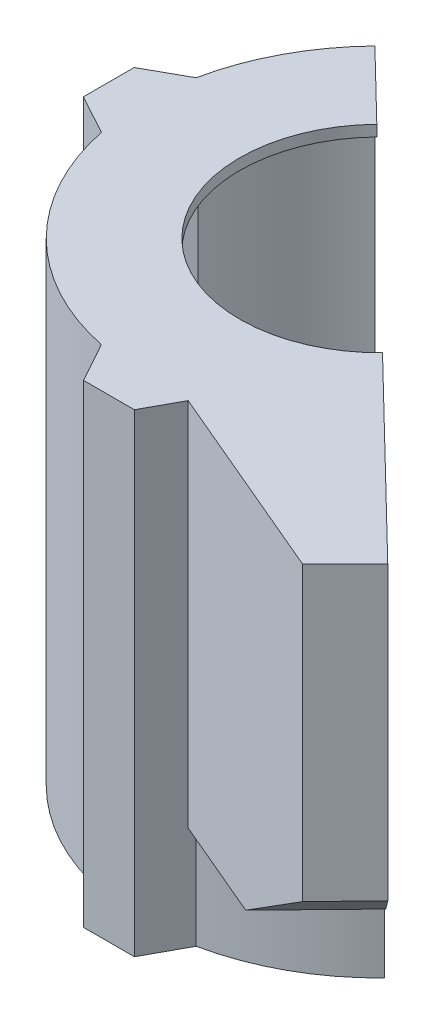
SolidWorks part; units mm, degrees
ref_plane "Alzado" through (0, 0, 0) normal (0, 0, 1) x (1, 0, 0)
ref_plane "Planta" through (0, 0, 0) normal (0, 1, 0) x (1, 0, 0)
ref_plane "Vista lateral" through (0, 0, 0) normal (1, 0, 0) x (0, 0, -1)
sketch "Croquis1" plane through (0, 0, 0) normal (0, 1, 0) x (1, 0, 0)
  line L0 (4, 58) -> (8.8071, 49.2182)
  line L1 (-4, 58) -> (4, 58)
  line L7 (-4, 58) -> (-8.8071, 49.2182)
  line L8 (58, 4) -> (58, -4)
  line L9 (58, 4) -> (49.2182, 8.8071)
  line L10 (58, -4) -> (49.2182, -8.8071)
  line L11 (4, -58) -> (-4, -58)
  line L12 (4, -58) -> (8.8071, -49.2182)
  line L13 (-4, -58) -> (-8.8071, -49.2182)
  line L14 (-58, -4) -> (-58, 4)
  line L15 (-58, -4) -> (-49.2182, -8.8071)
  line L16 (-58, 4) -> (-49.2182, 8.8071)
  arc A0 (-8.8071, 49.2182) -> (-49.2182, 8.8071) centre (0, 0) ccw
  arc A1 (-49.2182, -8.8071) -> (-8.8071, -49.2182) centre (0, 0) ccw
  arc A2 (49.2182, 8.8071) -> (8.8071, 49.2182) centre (0, 0) ccw
  arc A3 (8.8071, -49.2182) -> (49.2182, -8.8071) centre (0, 0) ccw
  point P3 (0, 50)
  point P25 (0, 0)
  dimension "D1" = 100
  dimension "D3" = 8
  dimension "D4" = 4
extrude "Saliente-Extruir1" add sketch "Croquis1" along normal blind 5
sketch "Croquis2" plane through (0, 5, 0) normal (0, 1, 0) x (1, 0, 0)
  line L0 (4, 58) -> (-4, 58) construction
  circle A0 centre (0, 52.7) radius 2.1
  circle A1 centre (52.7, 0) radius 2.1
  circle A2 centre (0, -52.7) radius 2.1
  circle A3 centre (-52.7, 0) radius 2.1
  point P13 (0, 0)
  dimension "D1" = 4.2
  dimension "D2" = 5.3
  dimension "D4" = 0
  dimension "D5" = 52.7
  dimension "D3" = 4
extrude "Cortar-Extruir1" cut sketch "Croquis2" against normal through all
cosmetic thread "Rosca cosmética5" parameters "D2"=5
cosmetic thread "Rosca cosmética6" parameters "D2"=5
cosmetic thread "Rosca cosmética7" parameters "D2"=5
cosmetic thread "Rosca cosmética8" parameters "D2"=5
sketch "Croquis3" plane through (0, 5, 0) normal (0, 1, 0) x (1, 0, 0)
  line L0 (0, 0) -> (33.9411, -33.9411) construction
  line L11 (20.5061, -34.6482) -> (34.6482, -20.5061)
  line L16 (20.5061, -34.6482) -> (33.234, -47.3762)
  line L23 (34.6482, -20.5061) -> (47.3762, -33.234)
  line L24 (20.5061, -34.6482) -> (47.3762, -33.234) construction
  line L25 (33.234, -47.3762) -> (34.6482, -20.5061) construction
  line L27 (33.234, -47.3762) -> (53.0768, -67.2189)
  line L28 (53.0768, -67.2189) -> (67.2189, -53.0768)
  line L29 (47.3762, -33.234) -> (67.2189, -53.0768)
  point P224 (33.9411, -56.9721)
  point P274 (21.2132, -31.2132)
  point P609 (21.2132, -48.2132)
  dimension "D1" = 18
  dimension "D2" = 20
  dimension "D3" = 48
extrude "Cortar-Extruir2" cut sketch "Croquis3" against normal through all
sketch "Croquis5" plane through (0, 5, 0) normal (0, 1, 0) x (1, 0, 0)
  line L9 (21.5541, -30.0393) -> (23.3345, -31.8198)
  line L11 (28.6251, -22.9683) -> (30.9862, -25.3293)
  line L12 (30.9862, -25.3293) -> (32.4004, -23.9151)
  line L13 (30.0393, -21.5541) -> (32.4004, -23.9151)
  line L14 (29.7686, -22.1503) -> (32.4004, -23.9151) construction
  line L15 (30.9862, -25.3293) -> (29.2214, -22.6975) construction
  line L17 (22.9683, -28.6251) -> (24.7487, -30.4056)
  line L20 (34.6482, -20.5061) -> (20.5061, -34.6482) construction
  line L21 (23.3345, -31.8198) -> (24.7487, -30.4056)
  line L22 (20.5061, -34.6482) -> (27.5699, -41.7121) construction
  line L23 (41.7121, -27.5699) -> (34.6482, -20.5061) construction
  circle A1 centre (-7.78, 7.78) radius 2.05
  circle A2 centre (7.78, 7.78) radius 2.05
  circle A3 centre (7.78, -7.78) radius 2.05
  circle A4 centre (-7.78, -7.78) radius 2.05
  arc A5 (30.0393, -21.5541) -> (28.6251, -22.9683) centre (28.1075, -21.0364) ccw
  arc A6 (22.9683, -28.6251) -> (21.5541, -30.0393) centre (21.0364, -28.1075) ccw
  point P13 (0, 0)
  dimension "D1" = 4.1
  dimension "D5" = 4
  dimension "D6" = 4
  dimension "D2" = 7.78
  dimension "D3" = 7.78
  dimension "D7" = 4.25
  dimension "D8" = 4.25
  dimension "D9" = 5
  dimension "D10" = 5
  dimension "D12" = 2
  dimension "D4" = 4
extrude "Cortar-Extruir4" cut sketch "Croquis5" against normal through all
cosmetic thread "Rosca cosmética1" parameters "D2"=5
cosmetic thread "Rosca cosmética2" parameters "D2"=5
cosmetic thread "Rosca cosmética3" parameters "D2"=5
cosmetic thread "Rosca cosmética4" parameters "D2"=5
sketch "Croquis7" plane through (0, 5, 0) normal (0, 1, 0) x (1, 0, 0)
  line L6 (68.5894, -54.4472) -> (54.4472, -68.5894)
  line L7 (48.7904, -62.9325) -> (62.9325, -48.7904)
  line L8 (68.5894, -54.4472) -> (49.2182, -8.8071)
  line L9 (34.6482, -20.5061) -> (31.8198, -23.3345) construction
  line L10 (48.7904, -62.9325) -> (27.5699, -41.7121)
  line L11 (62.9325, -48.7904) -> (41.7121, -27.5699)
  line L12 (41.7121, -27.5699) -> (46.423, -18.5717)
  line L13 (27.5699, -41.7121) -> (18.5717, -46.423)
  line L14 (49.2182, -8.8071) -> (46.423, -18.5717)
  line L15 (54.4472, -68.5894) -> (8.8071, -49.2182)
  line L16 (8.8071, -49.2182) -> (18.5717, -46.423)
  arc A0 (41.7121, -27.5699) -> (49.2182, -8.8071) centre (0, 0) ccw construction
  arc A1 (8.8071, -49.2182) -> (27.5699, -41.7121) centre (0, 0) ccw construction
  dimension "D1" = 8
  dimension "D2" = 40
extrude "Saliente-Extruir2" add sketch "Croquis7" against normal through all
sketch "Croquis8" plane through (0, 5, 0) normal (0, 1, 0) x (1, 0, 0)
  line L0 (62.9325, -48.7904) -> (48.7904, -62.9325) construction
  line L5 (54.2831, -59.94) -> (51.4902, -57.1471)
  line L6 (51.4902, -57.1471) -> (50.076, -58.5613)
  line L8 (55.8008, -67.5537) -> (55.1474, -63.8416) construction
  line L9 (55.8008, -56.19) -> (55.1474, -59.9021) construction
  line L11 (57.3718, -51.715) -> (58.7861, -50.3008)
  line L12 (57.3718, -51.715) -> (59.94, -54.2831)
  line L14 (58.7861, -50.3008) -> (61.3542, -52.8689)
  line L15 (54.4541, -59.9021) -> (53.8008, -56.19) construction
  line L18 (54.4541, -63.8416) -> (53.8008, -67.5537) construction
  line L19 (52.8689, -61.3542) -> (50.076, -58.5613)
  line L21 (62.9325, -48.7904) -> (48.7904, -62.9325) construction
  arc A3 (59.94, -54.2831) -> (61.3542, -52.8689) centre (61.8718, -54.8008) ccw
  arc A6 (52.8689, -61.3542) -> (54.2831, -59.94) centre (54.8008, -61.8718) ccw
  dimension "D1" = 4
  dimension "D3" = 3.5
  dimension "D4" = 3.5
  dimension "D7" = 2
  dimension "D8" = 2
extrude "Cortar-Extruir10" cut sketch "Croquis8" against normal through all
sketch "Croquis15" plane through (0, 0, 0) normal (0, -1, 0) x (1, 0, 0)
  line L2 (-1.1111, -20.4699) -> (-1.1111, -22.4725)
  line L4 (1.1111, -20.4699) -> (1.1111, -22.4725)
  arc A0 (1.1111, -22.4725) -> (-1.1111, -22.4725) centre (0, 0) ccw
  arc A1 (1.1111, -20.4699) -> (-1.1111, -20.4699) centre (0, 0) ccw
  point P4 (0, -19.25)
  dimension "D1" = 45
  dimension "D2" = 41
  dimension "D4" = 19.25
  dimension "D5" = 0
extrude "Saliente-Extruir4" add sketch "Croquis15" along normal blind 4
sketch "Croquis16" plane through (0, 0, 0) normal (0, -1, 0) x (1, 0, 0)
  line L0 (1.1111, -20.4699) -> (1.1111, -22.4725) construction
  line L1 (-1.1111, -20.4699) -> (-1.1111, -22.4725)
  line L2 (1.1111, -20.4699) -> (1.1111, -22.4725)
  arc A0 (-1.1111, -22.4725) -> (1.1111, -22.4725) centre (0, 0) ccw
  arc A1 (1.1111, -22.4725) -> (-1.1111, -22.4725) centre (0, 0) ccw construction
  arc A2 (-1.1111, -20.4699) -> (1.1111, -20.4699) centre (0, 0) ccw
extrude "Saliente-Extruir5" add sketch "Croquis16" along normal blind 4
sketch "Croquis17" plane through (0, 0, 0) normal (0, -1, 0) x (1, 0, 0)
  line L2 (0, 0) -> (42.43, 0) construction
  circle A2 centre (42.43, 0) radius 2.4
  circle A3 centre (0, -42.43) radius 2.4
  circle A4 centre (-42.43, 0) radius 2.4
  circle A5 centre (0, 42.43) radius 2.4
  point P13 (0, 0)
  dimension "D1" = 42.43
  dimension "D2" = 4
  dimension "D4" = 4.8
extrude "Cortar-Extruir11" cut sketch "Croquis17" against normal through all
sketch "Croquis18" plane through (0, 5, 0) normal (0, 1, 0) x (1, 0, 0)
  line L0 (61.5183, -61.5183) -> (-35.3553, 35.3553) construction
  line L1 (54.4472, -68.5894) -> (68.5894, -54.4472) construction
  line L2 (8.8071, -49.2182) -> (54.4472, -68.5894) construction
  line L3 (54.4472, -68.5894) -> (74.2597, -76.9984) construction
  line L4 (-4.4778, 59) -> (4.4778, 59)
  line L6 (5.0283, 57.9936) -> (9.3256, 50.1372) construction
  line L7 (0, 58) -> (0, 59) construction
  line L8 (4, 58) -> (-4, 58) construction
  line L9 (61.5183, -61.5183) -> (62.2254, -62.2254) construction
  line L10 (5.0283, 57.9936) -> (9.3256, 50.1372)
  line L12 (5.0283, 57.9936) -> (4.4778, 59)
  line L13 (4.4778, 59) -> (9.3256, 50.1372)
  line L14 (-4.4778, 59) -> (-9.3043, 50.1441)
  line L15 (59.0123, 4.481) -> (50.1388, 9.3171)
  line L16 (59.0123, 4.481) -> (59.0123, -4.4746)
  line L17 (58.006, -5.0251) -> (59.0123, -4.4746)
  line L18 (58.006, -5.0251) -> (50.4529, -9.1565)
  line L19 (69.7734, -54.6774) -> (54.6774, -69.7734)
  line L20 (4.4933, -59.0092) -> (9.1565, -50.4529)
  line L21 (4.4933, -59.0092) -> (-4.4623, -59.0092)
  line L22 (-5.0128, -58.0028) -> (-4.4623, -59.0092)
  line L23 (-5.0128, -58.0028) -> (-9.3121, -50.1426)
  line L24 (8.8071, -49.2182) -> (74.8349, -77.2425) construction
  line L25 (-58.9968, -4.4901) -> (-50.1419, -9.3161)
  line L26 (-58.9968, -4.4901) -> (-58.9968, 4.4655)
  line L27 (-57.9905, 5.0159) -> (-58.9968, 4.4655)
  line L28 (-57.9905, 5.0159) -> (-50.1434, 9.3082)
  line L29 (31.6271, -58.9038) -> (31.2364, -59.8243) construction
  line L30 (-7.0262, 59.1808) -> (-10.7128, 52.4165)
  line L31 (0, 59) -> (0, 61.5) construction
  line L32 (5.7622, 61.5) -> (-5.7622, 61.5)
  line L33 (-7.0262, 59.1808) -> (-5.7622, 61.5)
  line L34 (7.0262, 59.1808) -> (10.8312, 52.3921)
  line L35 (7.0262, 59.1808) -> (5.7622, 61.5)
  line L36 (59.2043, 7.0699) -> (52.4034, 10.7764)
  line L37 (59.2043, 7.0699) -> (61.5235, 5.8059)
  line L38 (61.5235, -5.7185) -> (61.5235, 5.8059)
  line L39 (59.2043, -6.9825) -> (61.5235, -5.7185)
  line L40 (59.2043, -6.9825) -> (53.5832, -10.133)
  line L41 (7.0934, -59.1606) -> (10.133, -53.5832)
  line L42 (7.0934, -59.1606) -> (5.8294, -61.4798)
  line L43 (-5.695, -61.4798) -> (5.8294, -61.4798)
  line L44 (-6.959, -59.1606) -> (-5.695, -61.4798)
  line L45 (-6.959, -59.1606) -> (-10.7424, -52.4104)
  line L46 (-59.1371, -7.0497) -> (-52.4166, -10.7124)
  line L47 (-59.1371, -7.0497) -> (-61.4563, -5.7857)
  line L48 (-61.4563, 5.7387) -> (-61.4563, -5.7857)
  line L49 (-59.1371, 7.0027) -> (-61.4563, 5.7387)
  line L50 (-59.1371, 7.0027) -> (-52.4033, 10.777)
  line L51 (7.7955, -49.8752) -> (54.6774, -69.7734) construction
  line L52 (54.6774, -69.7734) -> (11.945, -51.6364)
  line L53 (31.2364, -59.8243) -> (30.2597, -62.1256) construction
  line L54 (62.2254, -62.2254) -> (63.9932, -63.9932) construction
  line L55 (72.7335, -55.2528) -> (55.2528, -72.7335)
  line L56 (5.4308, -51.5874) -> (55.0886, -72.6638) construction
  line L57 (10.133, -53.5832) -> (55.2528, -72.7335)
  line L58 (69.7734, -54.6774) -> (51.6364, -11.945)
  line L59 (53.5832, -10.133) -> (72.7335, -55.2528)
  line L60 (11.945, -51.6364) -> (9.1565, -50.4529)
  line L61 (51.6364, -11.945) -> (50.4529, -9.1565)
  line L62 (63.1584, -32.6929) -> (60.8571, -33.6697) construction
  arc A0 (-8.8071, 49.2182) -> (-49.2182, 8.8071) centre (0, 0) ccw construction
  arc A2 (-9.3043, 50.1441) -> (-50.1434, 9.3082) centre (0, 0) ccw
  arc A3 (-10.7128, 52.4165) -> (-52.4033, 10.777) centre (0, 0) ccw
  arc A6 (-50.1419, -9.3161) -> (-9.3121, -50.1426) centre (0, 0) ccw
  arc A7 (-52.4166, -10.7124) -> (-10.7424, -52.4104) centre (0, 0) ccw
  arc A11 (50.1388, 9.3171) -> (9.3256, 50.1372) centre (0, 0) ccw
  arc A12 (52.4034, 10.7764) -> (10.8312, 52.3921) centre (0, 0) ccw
  point P54 (0.0078, -0.0046)
  point P80 (0.0336, 0.0101)
  dimension "D1" = 102
  dimension "D2" = 107
  dimension "D12" = 53.5
  dimension "D4" = 1
  dimension "D7" = 2.5
  dimension "D3" = 1
  dimension "D9" = 1
  dimension "D10" = 2.5
  dimension "D11" = 2.5
  dimension "D6" = 2
  dimension "D5" = 4
  dimension "D8" = 4
extrude "Saliente-Extruir6" add sketch "Croquis18" along normal blind 105 contours L40 L59 L55 L57 L41 L42 L43 L44 L45 A7 L46 L47 L48 L49 L50 A3 L30 L33 L32 L35 L34 A12 L36 L37 L38 L39
sketch "Croquis23" plane through (0, -4, 0) normal (0, -1, 0) x (1, 0, 0)
  line L8 (59, -4.5926) -> (58.9589, -4.6151)
  line L10 (-4.5926, -59) -> (-4.6151, -58.9589)
  line L17 (-4.5926, 59) -> (-4.6151, 58.9589)
  line L18 (4.5926, 59) -> (4.6151, 58.9589)
  line L19 (-4.5926, 59) -> (4.5926, 59)
  line L20 (-59, 4.5926) -> (-58.9589, 4.6151)
  line L21 (59, 4.5926) -> (58.9589, 4.6151)
  line L22 (4.5926, -59) -> (4.6151, -58.9589)
  line L23 (31.2364, 59.8243) -> (57.1595, 70.8269) construction
  line L24 (72.7335, 55.2528) -> (55.2528, 72.7335) construction
  line L25 (31.2364, 59.8243) -> (9.2496, 50.4924) construction
  line L26 (-59, -4.5926) -> (-58.9589, -4.6151)
  line L27 (62.2254, 62.2254) -> (69.7734, 54.6774) construction
  line L29 (62.2254, 62.2254) -> (54.6774, 69.7734) construction
  line L30 (4.6151, 58.9589) -> (9.2496, 50.4924)
  line L31 (9.2496, 50.4924) -> (54.6774, 69.7734)
  line L32 (54.6774, 69.7734) -> (69.7734, 54.6774)
  line L33 (50.4924, 9.2496) -> (69.7734, 54.6774)
  line L34 (-4.6151, 58.9589) -> (-9.2496, 50.4924)
  line L35 (59, 4.5926) -> (59, -4.5926)
  line L36 (58.9589, 4.6151) -> (50.4924, 9.2496)
  line L37 (58.9589, -4.6151) -> (50.4924, -9.2496)
  line L38 (4.5926, -59) -> (-4.5926, -59)
  line L39 (4.6151, -58.9589) -> (9.2496, -50.4924)
  line L40 (-4.6151, -58.9589) -> (-9.2496, -50.4924)
  line L41 (-59, -4.5926) -> (-59, 4.5926)
  line L42 (-58.9589, -4.6151) -> (-50.4924, -9.2496)
  line L43 (-58.9589, 4.6151) -> (-50.4924, 9.2496)
  line L45 (9.2496, 50.4924) -> (4.5926, 59) construction
  arc A3 (-9.2496, 50.4924) -> (-50.4924, 9.2496) centre (0, 0) ccw
  arc A5 (9.2496, -50.4924) -> (50.4924, -9.2496) centre (0, 0) ccw
  arc A7 (-50.4924, -9.2496) -> (-9.2496, -50.4924) centre (0, 0) ccw
  point P12 (0, 0)
  point P19 (0, 0)
  point P87 (0, 0)
  dimension "D1" = 4
  dimension "D2" = 4
  dimension "D5" = 4
extrude "Cortar-Extruir12" cut sketch "Croquis23" against normal blind 200
sketch "Croquis24" plane through (0, 5, 0) normal (0, -1, 0) x (1, 0, 0)
  line L0 (64.9124, 63.0739) -> (-49.9263, -48.5122) construction
  line L1 (72.7335, 55.2528) -> (55.2528, 72.7335) construction
  line L2 (-49.9263, -48.5122) -> (-1.3115, -98.5442) construction
  line L3 (-1.3115, -98.5442) -> (119.0784, 18.4358) construction
  line L4 (119.0784, 18.4358) -> (70.4635, 68.4677) construction
  line L5 (70.4635, 68.4677) -> (64.9124, 63.0739) construction
  line L6 (70.4635, 68.4677) -> (119.0784, 18.4358)
  line L7 (70.4635, 68.4677) -> (-49.9263, -48.5122)
  line L8 (119.0784, 18.4358) -> (-1.3115, -98.5442)
  line L9 (-49.9263, -48.5122) -> (-1.3115, -98.5442)
extrude "Cortar-Extruir13" cut sketch "Croquis24" against normal blind 200
sketch "Croquis27" plane through (0, 110, 0) normal (0, 1, 0) x (1, 0, 0)
  line L0 (0, 0) -> (0, -52.7) construction
  line L1 (2.2, -52.7) -> (3.8, -52.7) construction
  line L2 (-3.8, -52.7) -> (-3.8, -55.85)
  line L3 (-4.5926, -59) -> (4.5926, -59) construction
  line L4 (-4.1, -59) -> (4.1, -59)
  line L5 (3.8, -55.85) -> (3.8, -52.7)
  line L6 (3.8, -55.85) -> (5.5313, -57.2852)
  line L7 (4.5926, -59) -> (9.2496, -50.4924) construction
  line L8 (5.5313, -57.2852) -> (4.5926, -59)
  line L9 (4.5926, -59) -> (4.1, -59)
  line L10 (-4.5926, -59) -> (-4.1, -59)
  line L11 (-1.3, -52.7) -> (1.3, -52.7) construction
  line L12 (1.3, -52.7) -> (1.3, -50.9252) construction
  line L13 (-1.3, -52.7) -> (-1.3, -50.1293) construction
  line L14 (1.3, -50.1293) -> (1.3, -50.1722)
  line L15 (-1.3, -50.1293) -> (-1.3, -50.1722)
  line L16 (-5.5313, -57.2852) -> (-4.5926, -59)
  line L17 (-3.8, -55.85) -> (-5.5313, -57.2852)
  line L18 (-52.7, 3.8) -> (-55.85, 3.8)
  line L19 (-55.85, 3.8) -> (-57.2852, 5.5313)
  line L20 (-57.2852, 5.5313) -> (-59, 4.5926)
  line L21 (-59, 4.5926) -> (-59, 4.1)
  line L22 (-59, 4.1) -> (-59, -4.1)
  line L23 (-59, -4.5926) -> (-59, -4.1)
  line L24 (-57.2852, -5.5313) -> (-59, -4.5926)
  line L25 (-55.85, -3.8) -> (-57.2852, -5.5313)
  line L26 (-55.85, -3.8) -> (-52.7, -3.8)
  line L27 (-50.1293, -1.3) -> (-50.1722, -1.3)
  line L28 (-50.1293, 1.3) -> (-50.1722, 1.3)
  line L51 (-5.5313, 57.2852) -> (-4.5926, 59) [skipped]
  line L52 (1.3, 49.1293) -> (1.3, 50.9252) [skipped]
  line L53 (-3.8, 55.85) -> (-5.5313, 57.2852) [skipped]
  line L54 (-1.3, 49.1293) -> (-1.3, 50.9252) [skipped]
  line L55 (4.1, 59) -> (-4.1, 59) [skipped]
  line L56 (-3.8, 55.85) -> (-3.8, 52.7) [skipped]
  line L57 (3.8, 52.7) -> (3.8, 55.85) [skipped]
  line L58 (8.2991, 52.2289) -> (5.6606, 57.049) [skipped]
  line L59 (4.5926, 59) -> (4.1, 59) [skipped]
  line L60 (3.8, 55.85) -> (5.5313, 57.2852) [skipped]
  line L61 (-4.5926, 59) -> (-4.1, 59) [skipped]
  line L62 (59, -4.1) -> (59, 4.1) [skipped]
  line L63 (49.1293, 1.3) -> (50.9252, 1.3) [skipped]
  line L64 (49.1293, -1.3) -> (50.9252, -1.3) [skipped]
  line L65 (55.85, 3.8) -> (52.7, 3.8) [skipped]
  line L66 (55.85, 3.8) -> (57.2852, 5.5313) [skipped]
  line L67 (52.7, -3.8) -> (55.85, -3.8) [skipped]
  line L68 (55.85, -3.8) -> (57.2852, -5.5313) [skipped]
  line L69 (57.2852, -5.5313) -> (59, -4.5926) [skipped]
  line L70 (59, -4.5926) -> (59, -4.1) [skipped]
  line L71 (59, 4.5926) -> (59, 4.1) [skipped]
  line L72 (57.2852, 5.5313) -> (59, 4.5926) [skipped]
  line L74 (-2.0492, -50.1293) -> (-2.0492, -51.0528) construction
  line L75 (1.3, -50.1293) -> (1.3, -50.1722)
  line L76 (1.3, -50.1722) -> (1.3, -50.1293) construction
  line L99 (-3.8, -52.7) -> (-3.8, -55.85)
  line L100 (-3.8, -55.85) -> (-5.5313, -57.2852)
  line L101 (-5.5313, -57.2852) -> (-4.5926, -59)
  line L102 (-4.5926, -59) -> (-4.1, -59)
  line L103 (-4.1, -59) -> (4.1, -59)
  line L104 (4.5926, -59) -> (4.1, -59)
  line L105 (5.5313, -57.2852) -> (4.5926, -59)
  line L106 (3.8, -55.85) -> (5.5313, -57.2852)
  line L107 (3.8, -55.85) -> (3.8, -52.7)
  line L108 (1.3, -50.1293) -> (1.3, -50.1722)
  line L109 (-1.3, -50.1293) -> (-1.3, -50.1722)
  line L110 (3.8, 52.7) -> (3.8, 55.85) [skipped]
  line L111 (3.8, 55.85) -> (5.5313, 57.2852) [skipped]
  line L112 (5.5313, 57.2852) -> (4.5926, 59) [skipped]
  line L113 (4.5926, 59) -> (4.1, 59) [skipped]
  line L114 (4.1, 59) -> (-4.1, 59) [skipped]
  line L115 (-4.5926, 59) -> (-4.1, 59) [skipped]
  line L116 (-5.5313, 57.2852) -> (-4.5926, 59) [skipped]
  line L117 (-3.8, 55.85) -> (-5.5313, 57.2852) [skipped]
  line L118 (-3.8, 55.85) -> (-3.8, 52.7) [skipped]
  line L119 (-1.3, 50.1293) -> (-1.3, 50.1722) [skipped]
  line L120 (1.3, 50.1293) -> (1.3, 50.1722) [skipped]
  line L121 (52.7, -3.8) -> (55.85, -3.8) [skipped]
  line L122 (55.85, -3.8) -> (57.2852, -5.5313) [skipped]
  line L123 (57.2852, -5.5313) -> (59, -4.5926) [skipped]
  line L124 (59, -4.5926) -> (59, -4.1) [skipped]
  line L125 (59, -4.1) -> (59, 4.1) [skipped]
  line L126 (59, 4.5926) -> (59, 4.1) [skipped]
  line L127 (57.2852, 5.5313) -> (59, 4.5926) [skipped]
  line L128 (55.85, 3.8) -> (57.2852, 5.5313) [skipped]
  line L129 (55.85, 3.8) -> (52.7, 3.8) [skipped]
  line L130 (50.1293, 1.3) -> (50.1722, 1.3) [skipped]
  line L131 (50.1293, -1.3) -> (50.1722, -1.3) [skipped]
  arc A1 (-1.705, -51.3097) -> (1.705, -51.3097) centre (0, -52.7) ccw
  arc A2 (3.8, -52.7) -> (2.7985, -50.1293) centre (0, -52.7) ccw
  arc A3 (-2.7985, -50.1293) -> (-3.8, -52.7) centre (0, -52.7) ccw
  arc A4 (-52.7, -3.8) -> (-50.1293, -2.7985) centre (-52.7, 0) ccw
  arc A5 (-51.3097, 1.705) -> (-51.3097, -1.705) centre (-52.7, 0) ccw
  arc A6 (-50.1293, 2.7985) -> (-52.7, 3.8) centre (-52.7, 0) ccw
  arc A13 (1.3, 50.9252) -> (-1.3, 50.9252) centre (0, 52.7) ccw [skipped]
  arc A14 (1.3, 49.1293) -> (3.8, 52.7) centre (0, 52.7) ccw [skipped]
  arc A15 (-3.8, 52.7) -> (-1.3, 49.1293) centre (0, 52.7) ccw [skipped]
  arc A16 (50.9252, -1.3) -> (50.9252, 1.3) centre (52.7, 0) ccw [skipped]
  arc A17 (52.7, 3.8) -> (49.1293, 1.3) centre (52.7, 0) ccw [skipped]
  arc A18 (49.1293, -1.3) -> (52.7, -3.8) centre (52.7, 0) ccw [skipped]
  arc A19 (-1.3, -50.1722) -> (-1.705, -51.3097) centre (-3.1, -50.1722) cw
  arc A20 (-1.3, -50.1293) -> (-2.7985, -50.1293) centre (-2.0492, -51.0528) ccw
  arc A21 (1.3, -50.1722) -> (1.705, -51.3097) centre (3.1, -50.1722) ccw
  arc A22 (1.3, -50.1293) -> (2.7985, -50.1293) centre (2.0492, -51.0528) cw
  arc A23 (-50.1722, 1.3) -> (-51.3097, 1.705) centre (-50.1722, 3.1) cw
  arc A24 (-50.1293, 1.3) -> (-50.1293, 2.7985) centre (-51.0528, 2.0492) ccw
  arc A25 (-50.1722, -1.3) -> (-51.3097, -1.705) centre (-50.1722, -3.1) ccw
  arc A26 (-50.1293, -1.3) -> (-50.1293, -2.7985) centre (-51.0528, -2.0492) cw
  arc A35 (1.3, 50.1722) -> (1.705, 51.3097) centre (3.1, 50.1722) cw [skipped]
  arc A36 (1.3, 50.1293) -> (2.7985, 50.1293) centre (2.0492, 51.0528) ccw [skipped]
  arc A37 (-1.3, 50.1722) -> (-1.705, 51.3097) centre (-3.1, 50.1722) ccw [skipped]
  arc A38 (-1.3, 50.1293) -> (-2.7985, 50.1293) centre (-2.0492, 51.0528) cw [skipped]
  arc A39 (50.1722, -1.3) -> (51.3097, -1.705) centre (50.1722, -3.1) cw [skipped]
  arc A40 (50.1293, -1.3) -> (50.1293, -2.7985) centre (51.0528, -2.0492) ccw [skipped]
  arc A41 (50.1722, 1.3) -> (51.3097, 1.705) centre (50.1722, 3.1) ccw [skipped]
  arc A42 (50.1293, 1.3) -> (50.1293, 2.7985) centre (51.0528, 2.0492) cw [skipped]
  arc A49 (3.8, -52.7) -> (2.7985, -50.1293) centre (0, -52.7) ccw
  arc A50 (-1.705, -51.3097) -> (1.705, -51.3097) centre (0, -52.7) ccw
  arc A51 (-2.7985, -50.1293) -> (-3.8, -52.7) centre (0, -52.7) ccw
  arc A52 (-1.3, -50.1722) -> (-1.705, -51.3097) centre (-3.1, -50.1722) cw
  arc A53 (-1.3, -50.1293) -> (-2.7985, -50.1293) centre (-2.0492, -51.0528) ccw
  arc A54 (1.3, -50.1722) -> (1.705, -51.3097) centre (3.1, -50.1722) ccw
  arc A55 (1.3, -50.1293) -> (2.7985, -50.1293) centre (2.0492, -51.0528) cw
  arc A56 (-3.8, 52.7) -> (-2.7985, 50.1293) centre (0, 52.7) ccw [skipped]
  arc A57 (1.705, 51.3097) -> (-1.705, 51.3097) centre (0, 52.7) ccw [skipped]
  arc A58 (2.7985, 50.1293) -> (3.8, 52.7) centre (0, 52.7) ccw [skipped]
  arc A59 (1.3, 50.1722) -> (1.705, 51.3097) centre (3.1, 50.1722) cw [skipped]
  arc A60 (1.3, 50.1293) -> (2.7985, 50.1293) centre (2.0492, 51.0528) ccw [skipped]
  arc A61 (-1.3, 50.1722) -> (-1.705, 51.3097) centre (-3.1, 50.1722) ccw [skipped]
  arc A62 (-1.3, 50.1293) -> (-2.7985, 50.1293) centre (-2.0492, 51.0528) cw [skipped]
  arc A63 (52.7, 3.8) -> (50.1293, 2.7985) centre (52.7, 0) ccw [skipped]
  arc A64 (51.3097, -1.705) -> (51.3097, 1.705) centre (52.7, 0) ccw [skipped]
  arc A65 (50.1293, -2.7985) -> (52.7, -3.8) centre (52.7, 0) ccw [skipped]
  arc A66 (50.1722, -1.3) -> (51.3097, -1.705) centre (50.1722, -3.1) cw [skipped]
  arc A67 (50.1293, -1.3) -> (50.1293, -2.7985) centre (51.0528, -2.0492) ccw [skipped]
  arc A68 (50.1722, 1.3) -> (51.3097, 1.705) centre (50.1722, 3.1) ccw [skipped]
  arc A69 (50.1293, 1.3) -> (50.1293, 2.7985) centre (51.0528, 2.0492) cw [skipped]
  point P43 (-1.3, -50.9252)
  point P73 (0, 0)
  point P153 (0, 0)
  point P219 (0, 0)
  dimension "D1" = 4.4
  dimension "D3" = 1.6
  dimension "D6" = 1.8
  dimension "D2" = 52.7
  dimension "D4" = 1.3
  dimension "D5" = 4
  dimension "D7" = 4
  dimension "D8" = 4
extrude "Saliente-Extruir7" add sketch "Croquis27" against normal blind 93.5 contours L99 L100 L101 L102 L103 L104 L105 L106 L107 A49 A55 L108 A54 A50 A52 L109 A53 A51 | A5 A25 L27 A26 A4 L26 L25 L24 L23 L22 L21 L20 L19 L18 A6 A24 L28 A23
sketch "Croquis28" plane through (30.3278, 0, 16.5288) normal (0.8781, 0, 0.4785) x (0.4785, 0, -0.8781)
  line L1 (-51.1934, 5) -> (16.2157, 5)
  line L2 (-51.1934, 5) -> (-51.1934, 31)
  line L3 (-51.1934, 31) -> (16.2157, 31)
  line L4 (16.2157, 5) -> (16.2157, 31)
  dimension "D1" = 26
extrude "Cortar-Extruir15" cut sketch "Croquis28" along normal blind 104
sketch "Croquis35" plane through (0, 31, 0) normal (0, -1, 0) x (1, 0, 0)
  line L0 (36.8153, 35.7725) -> (64.9124, 63.0739)
  line L1 (64.9124, 63.0739) -> (55.2528, 72.7335)
  line L2 (55.2528, 72.7335) -> (10.133, 53.5832)
  line L5 (10.133, 53.5832) -> (9.2496, 50.4924)
  arc A0 (36.8153, 35.7725) -> (9.2496, 50.4924) centre (0, 0) ccw
extrude "Saliente-Extruir12" add sketch "Croquis35" along normal blind 2.5
sketch "Croquis36" plane through (0, 28.5, 0) normal (0, -1, 0) x (1, 0, 0)
  line L1 (36.8153, 35.7725) -> (64.9124, 63.0739) construction
  line L3 (36.8153, 35.7725) -> (38.3697, 37.2829)
  line L4 (36.8153, 35.7725) -> (64.9124, 63.0739) construction
  line L5 (9.2496, 50.4924) -> (7.9265, 52.9096)
  line L6 (4.5926, 59) -> (9.2496, 50.4924) construction
  arc A0 (36.8153, 35.7725) -> (9.2496, 50.4924) centre (0, 0) ccw
  arc A1 (38.3697, 37.2829) -> (7.9265, 52.9096) centre (0, 0) ccw
  arc A2 (36.8153, 35.7725) -> (9.2496, 50.4924) centre (0, 0) ccw
extrude "Saliente-Extruir13" add sketch "Croquis36" along normal blind 23.5 contours A1 L5 A0 L3
sketch "Croquis37" plane through (0, 0, 0) normal (0.6969, 0, -0.7172) x (-0.7172, 0, -0.6969)
  line L2 (-53.5, 28.5) -> (-63.5, 28.5) construction
  line L5 (-63.5, 28.5) -> (-90.5093, 28.5)
  line L9 (-53.5, 28.5) -> (-90.5093, 28.5) construction
  line L13 (-90.5093, 28.5) -> (-90.5093, 49.5)
  line L14 (-90.5093, 110) -> (-90.5093, 28.5) construction
  line L15 (-90.5093, 49.5) -> (-63.5, 28.5)
  dimension "D1" = 21
extrude "Cortar-Extruir20" cut sketch "Croquis37" against normal blind 50
sketch "Croquis44" plane through (0, 0, 0) normal (0.6969, 0, -0.7172) x (-0.7172, 0, -0.6969)
  line L0 (-90.5093, 49.5) -> (-63.5, 28.5)
  line L2 (-77.5012, 39.386) -> (-79.0357, 37.4124) construction
  line L3 (-63.5, 28.5) -> (-67.5729, 28.5)
  line L4 (-63.5, 28.5) -> (-66.7154, 31) construction
  line L5 (-79.0357, 37.4124) -> (-67.5729, 28.5)
  line L6 (-67.5729, 28.5) -> (-90.5093, 46.3333)
  line L8 (-90.5093, 49.5) -> (-90.5093, 46.3333)
  dimension "D1" = 2.5
extrude "Saliente-Extruir18" add sketch "Croquis44" against normal blind 30.5 contours L6 L8 L0 L3
sketch "Croquis45" plane through (-17.7242, 0, 41.7598) normal (-0.3907, 0, 0.9205) x (0.9205, 0, 0.3907)
  line L1 (36.7453, 68.3948) -> (81.8778, 68.3948)
  line L2 (36.7453, 68.3948) -> (36.7453, 15.2189)
  line L3 (36.7453, 15.2189) -> (81.8778, 15.2189)
  line L4 (81.8778, 68.3948) -> (81.8778, 15.2189)
extrude "Cortar-Extruir23" cut sketch "Croquis45" along normal blind 30.5
sketch "Croquis46" plane through (63.9932, 0, 63.9932) normal (0.7071, 0, 0.7071) x (0.7071, 0, -0.7071)
  line L1 (-18.8545, 61.1743) -> (6.9501, 61.1743)
  line L2 (-18.8545, 61.1743) -> (-18.8545, 35.5215)
  line L3 (-18.8545, 35.5215) -> (6.9501, 35.5215)
  line L4 (6.9501, 61.1743) -> (6.9501, 35.5215)
extrude "Cortar-Extruir24" cut sketch "Croquis46" along normal blind 30.5
sketch "Croquis47" plane through (0, 110, 0) normal (0, 1, 0) x (1, 0, 0)
  line L0 (-61.4563, 5.7387) -> (-61.4563, -5.7857) construction
  line L1 (-58.9573, 5.7387) -> (-58.9573, -5.7857) construction
  line L2 (-57.2852, -5.5313) -> (-58.9573, -4.617) construction
  line L3 (-57.2852, -5.5313) -> (-58.9573, -4.617)
  line L4 (-58.9573, -4.617) -> (-58.9573, -0.0235)
  line L5 (-58.9573, -0.0235) -> (-54.9, 0) construction
  line L6 (-57.349, 5.5033) -> (-59.0105, 4.5698)
  line L7 (-59.0105, 4.5698) -> (-58.9573, -0.0235)
  line L8 (-57.349, 5.5033) -> (-47.332, 5.5033)
  line L9 (-47.332, 5.5033) -> (-47.332, -5.5313)
  line L10 (-47.332, -5.5313) -> (-57.2852, -5.5313)
  line L33 (5.5308, -57.2848) -> (4.6166, -58.957)
  line L34 (4.6166, -58.957) -> (0.023, -58.957)
  line L35 (-5.5038, -57.3487) -> (-4.5703, -59.0101)
  line L36 (-4.5703, -59.0101) -> (0.023, -58.957)
  line L37 (-5.5038, -57.3487) -> (-5.5038, -47.3316)
  line L38 (-5.5038, -47.3316) -> (5.5308, -47.3316)
  line L39 (5.5308, -47.3316) -> (5.5308, -57.2848)
  line L40 (-5.7392, -61.4559) -> (5.7852, -61.4559) construction
  line L41 (-5.7392, -58.957) -> (5.7852, -58.957) construction
  line L42 (5.5308, -57.2848) -> (4.6166, -58.957) construction
  line L43 (0.023, -58.957) -> (-0.0005, -54.8996) construction
  line L44 (-5.5317, 57.2847) -> (-4.6174, 58.9568) [skipped]
  line L45 (-4.6174, 58.9568) -> (-0.0238, 58.9568) [skipped]
  line L46 (5.503, 57.3485) -> (4.5694, 59.01) [skipped]
  line L47 (4.5694, 59.01) -> (-0.0238, 58.9568) [skipped]
  line L48 (5.503, 57.3485) -> (5.503, 47.3315) [skipped]
  line L49 (5.503, 47.3315) -> (-5.5317, 47.3315) [skipped]
  line L50 (-5.5317, 47.3315) -> (-5.5317, 57.2847) [skipped]
  line L51 (5.7384, 61.4558) -> (-5.7861, 61.4558) construction
  line L52 (5.7384, 58.9568) -> (-5.7861, 58.9568) construction
  line L53 (-5.5317, 57.2847) -> (-4.6174, 58.9568) construction
  line L54 (-0.0238, 58.9568) -> (-0.0004, 54.8995) construction
  line L55 (57.2843, 5.5312) -> (58.9565, 4.6169) [skipped]
  line L56 (58.9565, 4.6169) -> (58.9565, 0.0233) [skipped]
  line L57 (57.3482, -5.5035) -> (59.0096, -4.5699) [skipped]
  line L58 (59.0096, -4.5699) -> (58.9565, 0.0233) [skipped]
  line L59 (57.3482, -5.5035) -> (47.3311, -5.5035) [skipped]
  line L60 (47.3311, -5.5035) -> (47.3311, 5.5312) [skipped]
  line L61 (47.3311, 5.5312) -> (57.2843, 5.5312) [skipped]
  line L62 (61.4554, -5.7389) -> (61.4554, 5.7856) construction
  line L63 (58.9565, -5.7389) -> (58.9565, 5.7856) construction
  line L64 (57.2843, 5.5312) -> (58.9565, 4.6169) construction
  line L65 (58.9565, 0.0233) -> (54.8991, -0.0001) construction
  arc A0 (-51.3097, 1.705) -> (-51.3097, -1.705) centre (-52.7, 0) ccw construction
  point P57 (-0.0004, -0.0001)
  dimension "D1" = 2
  dimension "D2" = 4
extrude "Cortar-Extruir26" cut sketch "Croquis47" against normal blind 59
sketch "Croquis48" plane through (0, 110, 0) normal (0, 1, 0) x (1, 0, 0)
  line L0 (-52.4033, 10.777) -> (-61.4563, 5.7387)
  line L1 (-61.4563, 5.7387) -> (-61.4563, -5.7857)
  line L2 (-61.4563, -5.7857) -> (-52.4166, -10.7124)
  line L3 (5.8294, -61.4798) -> (10.133, -53.5832)
  line L4 (-10.7424, -52.4104) -> (-5.695, -61.4798)
  line L5 (-5.695, -61.4798) -> (5.8294, -61.4798)
  line L6 (55.2528, -72.7335) -> (10.133, -53.5832)
  line L7 (55.2528, -72.7335) -> (64.9124, -63.0739)
  line L8 (64.9124, -63.0739) -> (22.7708, -22.1259)
  line L9 (-22.7708, 22.1259) -> (-38.3697, 37.2829)
  arc A0 (-52.4166, -10.7124) -> (-10.7424, -52.4104) centre (0, 0) ccw
  arc A1 (-38.3697, 37.2829) -> (-52.4033, 10.777) centre (0, 0) ccw
  arc A2 (-22.7708, 22.1259) -> (22.7708, -22.1259) centre (0, 0) ccw
  dimension "D1" = 63.5
extrude "Saliente-Extruir19" add sketch "Croquis48" along normal blind 2.5
sketch "Croquis49" plane through (0, 0, 0) normal (0.6969, 0, -0.7172) x (-0.7172, 0, -0.6969)
  line L1 (-88.0091, 110) -> (-89.3091, 110)
  line L2 (-88.0091, 110) -> (-88.0091, 47.556)
  line L3 (-88.0091, 47.556) -> (-89.3091, 47.556)
  line L4 (-89.3091, 110) -> (-89.3091, 47.556)
  dimension "D1" = 1.3
extrude "Cortar-Extruir27" cut sketch "Croquis49" against normal blind 2.5
sketch "Croquis50" plane through (0, 0, 0) normal (0.6969, 0, -0.7172) x (-0.7172, 0, -0.6969)
  line L0 (-88.0091, 110) -> (-81.0091, 110) construction
  line L5 (-88.0091, 110) -> (-31.75, 110) construction
  line L6 (-81.0091, 110) -> (-41.0091, 110)
  line L7 (-41.8208, 110) -> (-87.8376, 110) construction
  line L8 (-41.0091, 110) -> (-41.0091, 111.3)
  line L9 (-41.0091, 111.3) -> (-81.0091, 111.3)
  line L10 (-81.0091, 111.3) -> (-81.0091, 110)
  dimension "D1" = 7
  dimension "D2" = 1.3
  dimension "D3" = 40
extrude "Cortar-Extruir28" cut sketch "Croquis50" against normal blind 2.5
sketch "Croquis51" plane through (0, 0, 0) normal (0.6969, 0, -0.7172) x (-0.7172, 0, -0.6969)
  line L0 (35.75, 110) -> (35.75, 111.3)
  line L1 (31.75, 110) -> (51.3326, 110) construction
  line L2 (35.75, 111.3) -> (48.75, 111.3)
  line L3 (48.75, 111.3) -> (48.75, 110)
  line L4 (48.75, 110) -> (35.75, 110)
  line L5 (35.75, 110) -> (31.75, 110) construction
  dimension "D1" = 4
  dimension "D2" = 13
  dimension "D3" = 1.3
extrude "Cortar-Extruir29" cut sketch "Croquis51" against normal blind 2.5
